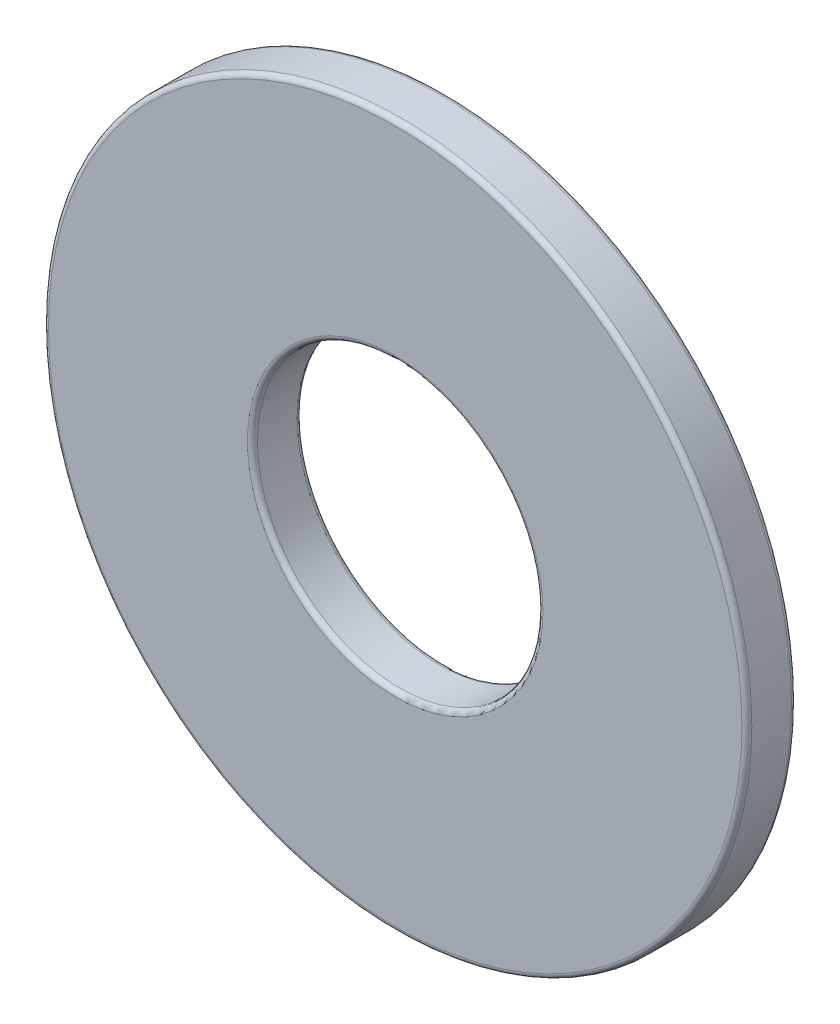
SolidWorks part; units mm, degrees
ref_plane "Front Plane" through (0, 0, 0) normal (0, 0, 1) x (1, 0, 0)
ref_plane "Top Plane" through (0, 0, 0) normal (0, 1, 0) x (1, 0, 0)
ref_plane "Right Plane" through (0, 0, 0) normal (1, 0, 0) x (0, 0, -1)
sketch "Sketch1" plane through (0, 0, 0) normal (0, 0, 1) x (1, 0, 0)
  circle A0 centre (0, 0) radius 25.4 construction
  circle A1 centre (0, 0) radius 10.3124 construction
  dimension "OD" = 50.8
  dimension "ID" = 20.6248
sketch "Sketch2" plane through (0, 0, 0) normal (1, 0, 0) x (0, 0, -1)
  line L0 (-1.7907, -25.4) -> (1.7907, -25.4) construction
  point P0 (1.2573, -25.4)
  point P4 (0, -25.4)
  dimension "Thickness Max" = 3.5814
  dimension "Thickness Min" = 3.048
sketch "Sketch3" plane through (0, 0, 0) normal (0, 0, 1) x (1, 0, 0)
  circle A0 centre (0, 0) radius 25.4 construction
  circle A1 centre (0, 0) radius 25.4
  circle A2 centre (0, 0) radius 10.3124 construction
  circle A3 centre (0, 0) radius 10.3124
extrude "Boss-Extrude1" add sketch "Sketch3" against normal up to vertex (1.7907 mm away) and the other way up to vertex (1.7907 mm away) up to point (0, -25.4, -1.7907) other way up to point (0, -25.4, 1.7907)
fillet "Fillet1" radius 0.3581 4 edges at (25.4, 0, -1.7907) (10.3124, 0, -1.7907) (10.3124, 0, 1.7907) (25.4, 0, 1.7907)
equation "\"D1@Fillet1\" = \"Thickness Max@Sketch2\" * 0.1"
